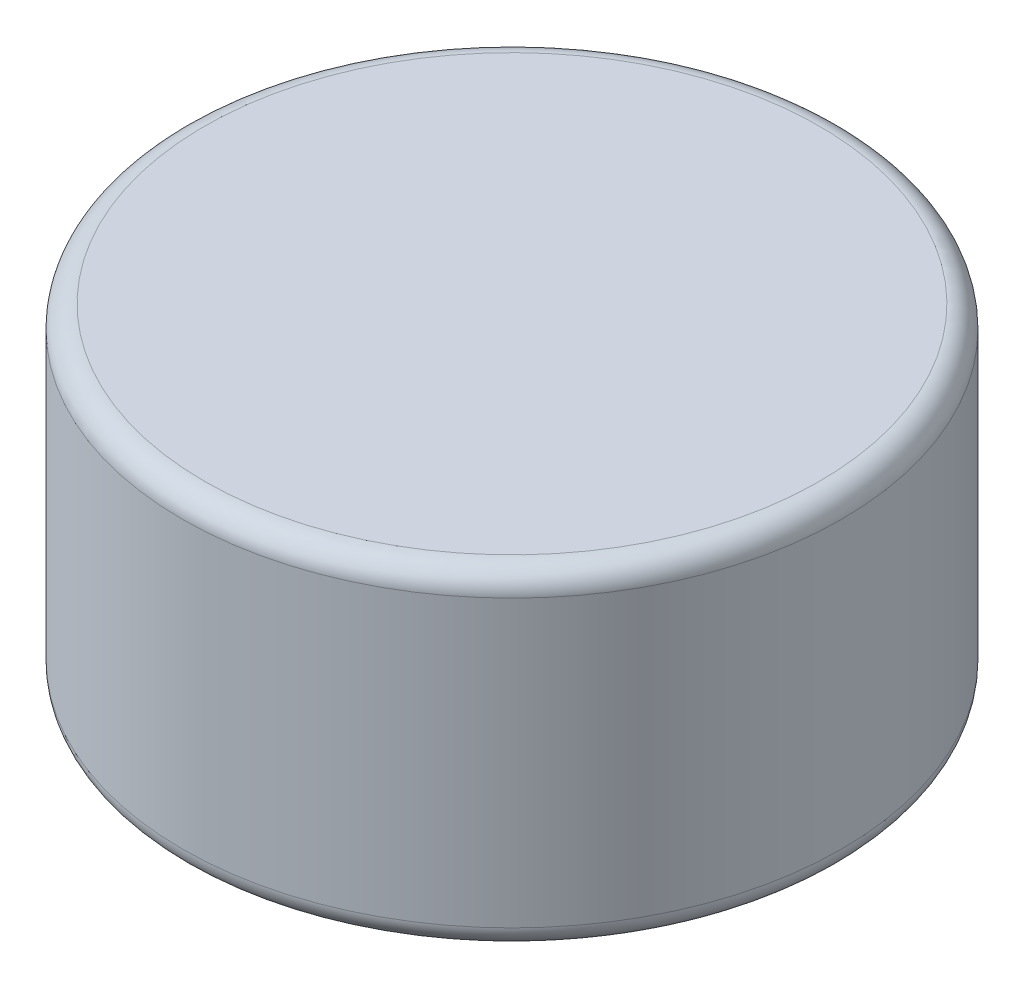
SolidWorks part; units mm, degrees
material "1023 Arkusz stali węglowej (SS)"
ref_plane "Płaszczyzna przednia" through (0, 0, 0) normal (0, 0, 1) x (1, 0, 0)
ref_plane "Płaszczyzna górna" through (0, 0, 0) normal (0, 1, 0) x (1, 0, 0)
ref_plane "Płaszczyzna prawa" through (0, 0, 0) normal (1, 0, 0) x (0, 0, -1)
sketch "Szkic1" plane through (0, 0, 0) normal (0, 1, 0) x (1, 0, 0)
  circle A0 centre (0, 0) radius 3
  dimension "D1" = 6
extrude "Dodanie-wyciągnięcie1" add sketch "Szkic1" along normal blind 3
fillet "Zaokrąglenie1" radius 0.2 2 edges at (0, 3, 3) (0, 0, 3)
